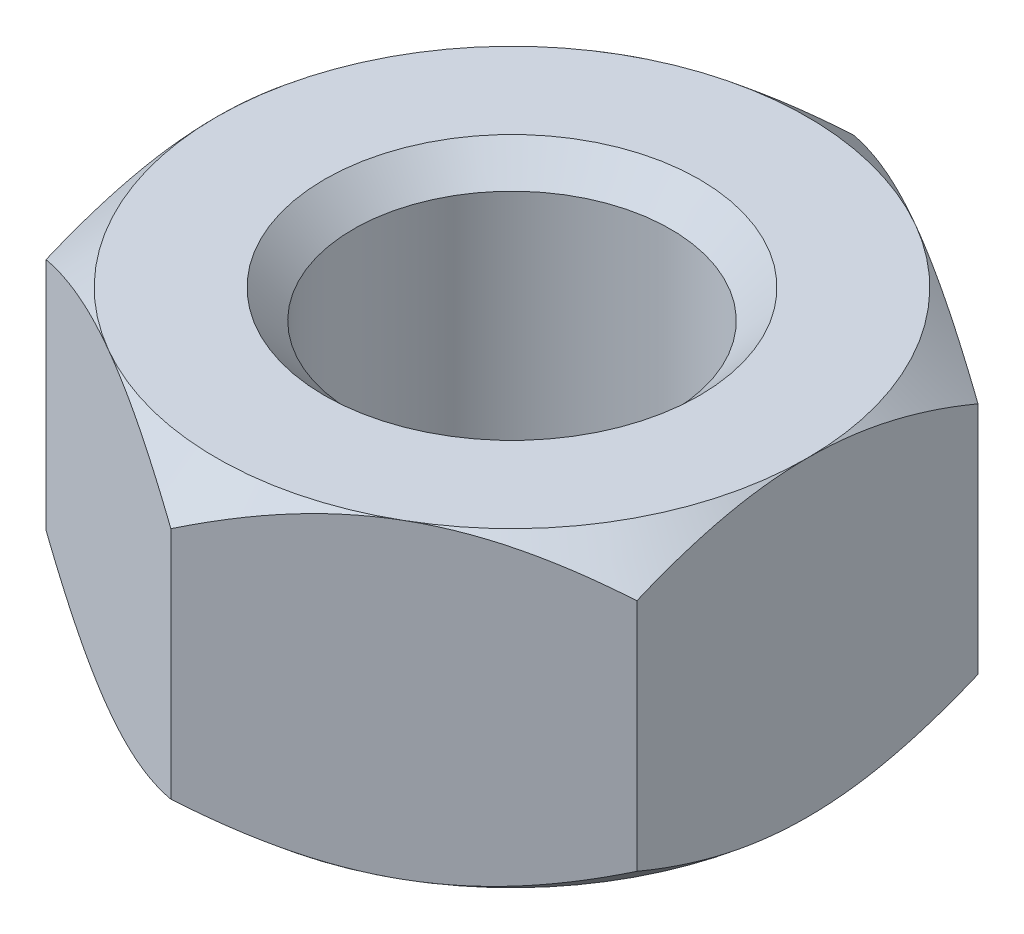
SolidWorks part; units mm, degrees
material "Galvanized Steel"
ref_plane "Front Plane" through (0, 0, 0) normal (0, 0, 1) x (1, 0, 0)
ref_plane "Top Plane" through (0, 0, 0) normal (0, 1, 0) x (1, 0, 0)
ref_plane "Right Plane" through (0, 0, 0) normal (1, 0, 0) x (0, 0, -1)
sketch "Sketch1" plane through (0, 0, 0) normal (0, 1, 0) x (1, 0, 0)
  line L1 (0, 10.9697) -> (-9.5, 5.4848)
  line L2 (-9.5, 5.4848) -> (-9.5, -5.4848)
  line L3 (-9.5, -5.4848) -> (0, -10.9697)
  line L4 (0, -10.9697) -> (9.5, -5.4848)
  line L5 (9.5, -5.4848) -> (9.5, 5.4848)
  line L6 (9.5, 5.4848) -> (0, 10.9697)
  circle A0 centre (0, 0) radius 9.5 construction
  dimension "D1" = 19
extrude "Boss-Extrude1" add sketch "Sketch1" along normal mid plane 10
hole_wizard "M12 Tapped Hole1" positions "Sketch3" profile "Sketch4" tap size "M12" standard "DIN" end condition through all
sketch "Sketch3" plane through (0, 5, 0) normal (0, 1, 0) x (1, 0, 0)
  point P0 (0, 0)
  point P4 (0, 0)
  point P5 (0, 0)
sketch "Sketch4" plane through (0, 5, 0) normal (1, 0, 0) x (0, 0, 1)
  line L0 (0, 0) -> (0, 10)
  line L1 (0, 10) -> (6.025, 10)
  line L2 (5.1, 9.075) -> (5.1, 0.925)
  line L3 (5.1, 0.925) -> (6.025, 0)
  line L5 (6.025, 0) -> (0, 0)
  line L6 (-5.1, 0.925) -> (-6.025, 0) construction
  line L7 (6.025, 10) -> (5.1, 9.075)
  line L8 (-6.025, 10) -> (-5.1, 9.075) construction
  line L11 (0, -6.35) -> (0, 107.95) construction
  dimension "Thru Tap Drill Dia." = 10.2
  dimension "Thru Tap Drill Depth" = 10
  dimension "Near C'Sink Dia." = 12.05
  dimension "Near C'Sink Angle" = 90
  dimension "Far C'Sink Dia." = 12.05
  dimension "Far C'Sink Angle" = 90
cosmetic thread "Hole Thread1" parameters "D2"=12
sketch "Sketch5" plane through (0, 5, 0) normal (0, 1, 0) x (1, 0, 0)
  circle A0 centre (0, 0) radius 9.5
extrude "Cut-Extrude1" cut sketch "Sketch5" against normal blind 10 draft 50 flip side to cut
mirror "Mirror1" about plane through (0, 0, 0) normal (0, 1, 0) of "Cut-Extrude1"
